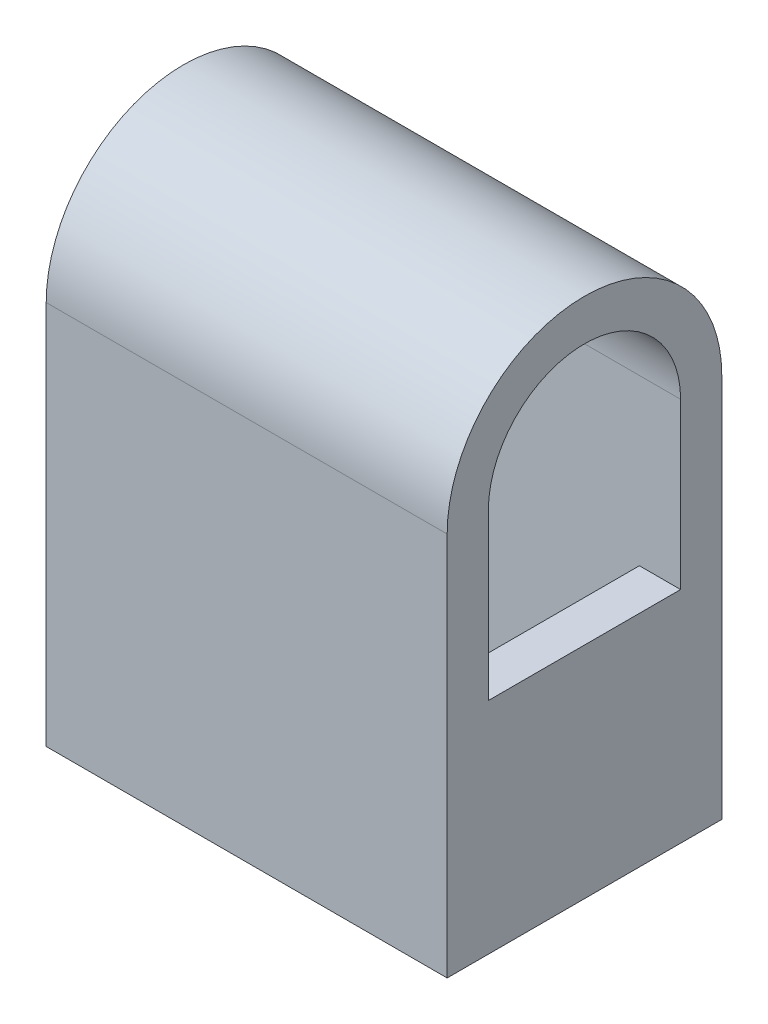
SolidWorks part; units mm, degrees
ref_plane "Front Plane" through (0, 0, 0) normal (0, 0, 1) x (1, 0, 0)
ref_plane "Top Plane" through (0, 0, 0) normal (0, 1, 0) x (1, 0, 0)
ref_plane "Right Plane" through (0, 0, 0) normal (1, 0, 0) x (0, 0, -1)
sketch "Sketch1" plane through (0, 0, 0) normal (0, 0, 1) x (1, 0, 0)
  line L1 (-9.271, -8.89) -> (9.271, -8.89)
  line L2 (-9.271, -8.89) -> (-9.271, 8.89)
  line L3 (-9.271, 8.89) -> (9.271, 8.89)
  line L4 (9.271, -8.89) -> (9.271, 8.89)
  line L5 (-9.271, -8.89) -> (9.271, 8.89) construction
  line L6 (-9.271, 8.89) -> (9.271, -8.89) construction
  point P0 (0, 0)
  dimension "D1" = 17.78
  dimension "D2" = 18.542
ref_plane "Plane2" through (0, 0, -12.7) normal (0, 0, 1) x (1, 0, 0)
sketch "Sketch4" plane through (0, 0, -12.7) normal (0, 0, 1) x (1, 0, 0)
  line L1 (9.271, -8.89) -> (-9.271, -8.89)
  line L2 (9.271, -8.89) -> (9.271, 8.89)
  line L3 (9.271, 8.89) -> (-9.271, 8.89)
  line L4 (-9.271, -8.89) -> (-9.271, 8.89)
  line L5 (9.271, -8.89) -> (-9.271, 8.89) construction
  line L6 (9.271, 8.89) -> (-9.271, -8.89) construction
  point P0 (0, 0)
extrude "Boss-Extrude4" add sketch "Sketch1" against normal blind 1.905
extrude "Boss-Extrude5" add sketch "Sketch4" along normal blind 1.905 separate body
ref_plane "Plane3" through (0, 0, -6.35) normal (0, 0, 1) x (1, 0, 0)
ref_plane "Plane4" through (0, 8.89, 0) normal (0, 1, 0) x (1, 0, 0)
ref_plane "Plane5" through (-9.271, 0, 0) normal (-1, 0, 0) x (0, 0, 1)
sketch "Sketch6" plane through (-9.271, 0, 0) normal (-1, 0, 0) x (0, 0, 1)
  line L0 (-12.7, 0) -> (0, 0) construction
  line L1 (-12.7, -5.4994) -> (-12.7, 5.4994) construction
  line L2 (-1.905, 8.89) -> (-1.905, -8.89) construction
  line L3 (10.1981, 8.89) -> (-10.1981, 8.89) construction
  line L4 (-6.35, 8.89) -> (-6.35, 7.62) construction
  line L5 (-10.795, 8.89) -> (-12.7, 8.89) construction
  line L6 (-12.7, 8.89) -> (-10.795, 8.89)
  line L7 (-1.905, 8.89) -> (0, 8.89)
  arc A0 (-10.795, 8.89) -> (-1.905, 8.89) centre (-6.35, 8.89) cw
  arc A1 (0, 8.89) -> (-12.7, 8.89) centre (-6.35, 8.89) ccw
extrude "Boss-Extrude6" add sketch "Sketch6" against normal up to surface (18.542 mm away) up to face at (9.271, 0, -0.9525)
sketch "Sketch7" plane through (-9.271, 0, 0) normal (-1, 0, 0) x (0, 0, 1)
  line L0 (-1.905, 8.89) -> (-1.905, -8.89) construction
  line L1 (-10.795, -8.89) -> (-1.905, -8.89)
  line L2 (-10.795, -8.89) -> (-10.795, 1.27)
  line L3 (-10.795, 1.27) -> (-1.905, 1.27)
  line L4 (-1.905, -8.89) -> (-1.905, 1.27)
  dimension "D1" = 10.16
extrude "Boss-Extrude7" add sketch "Sketch7" against normal blind 1.905
ref_plane "Plane8" through (0, 0, 0) normal (-1, 0, 0) x (0, 0, 1)
ref_plane "Plane9" through (9.271, 0, 0) normal (1, 0, 0) x (0, 0, -1)
sketch "Sketch8" plane through (9.271, 0, 0) normal (1, 0, 0) x (0, 0, -1)
  line L5 (1.905, -8.89) -> (10.795, -8.89)
  line L6 (1.905, -8.89) -> (1.905, 1.27)
  line L7 (1.905, 1.27) -> (10.795, 1.27)
  line L8 (10.795, -8.89) -> (10.795, 1.27)
extrude "Boss-Extrude8" add sketch "Sketch8" against normal blind 1.905
sketch "Sketch9" plane through (9.271, 0, 0) normal (1, 0, 0) x (0, 0, -1)
  line L0 (6.35, 1.27) -> (6.35, -8.89) construction
  line L1 (10.795, 1.27) -> (1.905, 1.27) construction
  line L2 (12.7, -8.89) -> (0, -8.89) construction
  line L3 (9.525, -3.81) -> (3.175, -3.81) construction
  line L5 (3.175, -3.81) -> (9.525, -3.81)
  line L6 (3.175, -3.81) -> (3.175, 1.27)
  line L7 (3.175, 1.27) -> (9.525, 1.27)
  line L8 (9.525, -3.81) -> (9.525, 1.27)
  point P9 (6.35, -3.81)
sketch "Sketch12" plane through (0, 0, -12.7) normal (0, 0, -1) x (-1, 0, 0)
  line L4 (0, -8.89) -> (0, 0) construction
  line L5 (-6.35, -8.89) -> (6.35, -8.89) construction
  line L7 (6.35, -8.89) -> (-6.35, -8.89)
  line L8 (-6.35, -8.89) -> (-6.35, 3.81)
  line L9 (-6.35, 3.81) -> (6.35, 3.81)
  line L10 (6.35, 3.81) -> (6.35, -8.89)
extrude "Boss-Extrude11" add sketch "Sketch12" along normal blind 2.286
sketch "Sketch13" plane through (0, 3.81, 0) normal (0, 1, 0) x (1, 0, 0)
  line L0 (0, 14.986) -> (0, 12.7) construction
  line L1 (-6.35, 14.986) -> (6.35, 14.986) construction
  line L2 (-6.7798, 12.7) -> (6.7798, 12.7) construction
  line L3 (5.08, 12.7) -> (-5.08, 12.7) construction
  line L4 (-6.35, 12.7) -> (6.35, 12.7) construction
  line L5 (-5.08, 12.7) -> (5.08, 12.7)
  line L6 (5.08, 12.7) -> (5.08, 14.478)
  line L7 (5.08, 14.478) -> (-5.08, 14.4207)
  line L8 (-5.08, 14.4207) -> (-5.08, 12.7)
extrude "Cut-Extrude2" cut sketch "Sketch13" against normal through all
